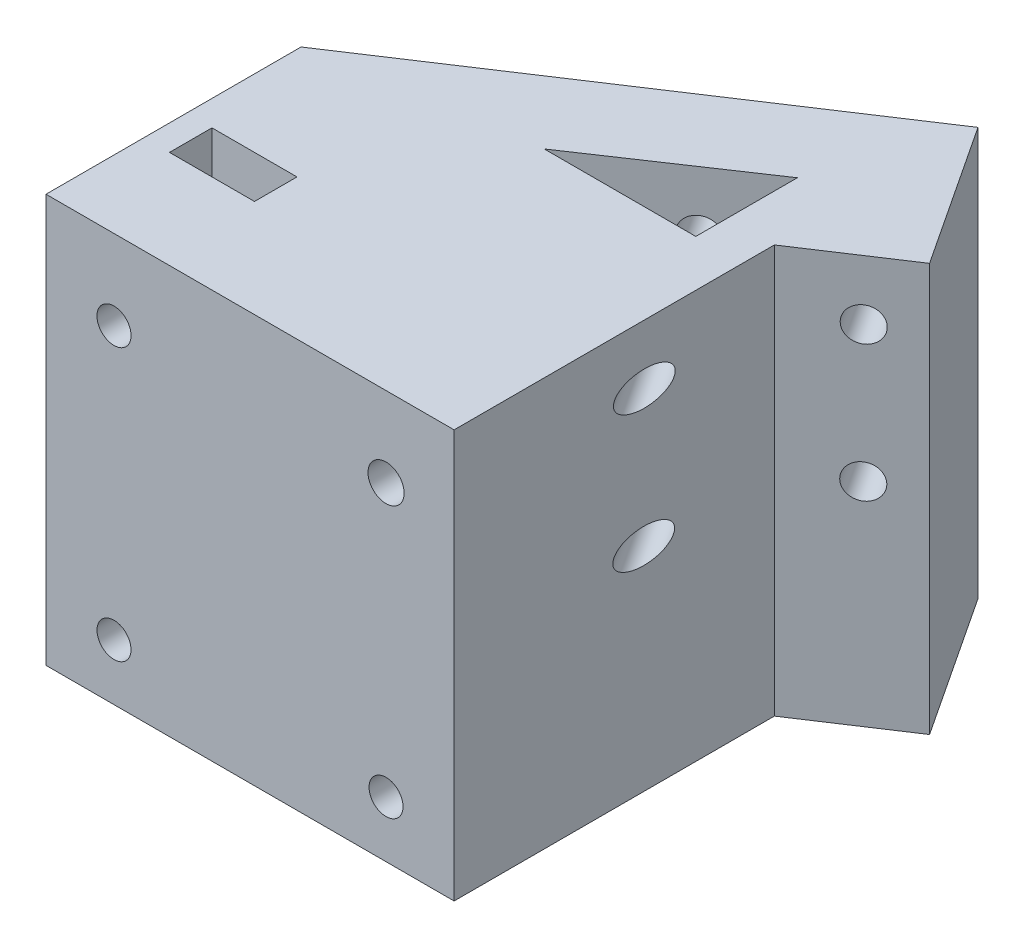
SolidWorks part; units mm, degrees
ref_plane "Front" through (0, 0, 0) normal (0, 0, 1) x (1, 0, 0)
ref_plane "Top" through (0, 0, 0) normal (0, 1, 0) x (1, 0, 0)
ref_plane "Right" through (0, 0, 0) normal (1, 0, 0) x (0, 0, -1)
sketch "Sketch1" plane through (0, 0, 0) normal (0, 1, 0) x (1, 0, 0)
  line L0 (48.006, 31.6253) -> (0, 0)
  line L1 (0, 0) -> (48.006, 0)
  line L2 (0, 0) -> (0, 31.6253)
  line L3 (0, 31.6253) -> (48.006, 31.6253)
  line L4 (48.006, 0) -> (48.006, 31.6253)
  dimension "D1" = 48.006
extrude "Boss-Extrude1" add sketch "Sketch1" along normal blind 48 contours L1 L4 L0
sketch "Sketch2" plane through (0, 0, 0) normal (0, 0, 1) x (1, 0, 0)
  line L1 (0, 0) -> (48.006, 0)
  line L2 (0, 0) -> (0, 48)
  line L3 (0, 48) -> (48.006, 48)
  line L4 (48.006, 0) -> (48.006, 48)
  circle A0 centre (8, 6.6) radius 2
  circle A1 centre (8, 38.6) radius 2.0068
  circle A2 centre (40, 6.6) radius 2
  circle A3 centre (40, 38.6) radius 2.1235
ref_plane "Plane2" through (0, 0, 0) normal (-0.5501, 0, -0.8351) x (-0.8351, 0, 0.5501)
sketch "Sketch4" plane through (0, 0, 0) normal (-0.5501, 0, -0.8351) x (-0.8351, 0, 0.5501)
  line L0 (-57.4868, 48) -> (-57.4868, 0) construction
  line L2 (-57.4868, 48) -> (0, 48) construction
  circle A0 centre (-51.8973, 40.9808) radius 2
  circle A1 centre (-42.4868, 33) radius 12.339
  circle A2 centre (-35.8955, 41.0209) radius 2
  circle A3 centre (-35.8554, 25.0192) radius 2
  circle A4 centre (-51.8571, 24.9791) radius 2
  point P17 (-43.8763, 33)
  dimension "D1" = 15
  dimension "D2" = 15
  dimension "D3" = 4
extrude "Cut-Extrude2" cut sketch "Sketch4" against normal blind 50 contours A4 | A0 | A2 | A3
extrude "Boss-Extrude2" add sketch "Sketch2" along normal blind 30
sketch "Sketch5" plane through (0, 0, 0) normal (-0.5501, 0, -0.8351) x (-0.8351, 0, 0.5501)
  circle A0 centre (-43.8571, 32.9791) radius 4
  circle A1 centre (-51.8571, 24.9791) radius 2 construction
  dimension "D1" = 8
  dimension "D2" = 8
  dimension "D3" = 8
extrude "Cut-Extrude3" cut sketch "Sketch5" against normal blind 6
sketch "Sketch6" plane through (0, 0, 0) normal (0, -1, 0) x (1, 0, 0)
  line L2 (24.6899, -3.9158) -> (42.5147, -3.9158)
  line L4 (24.6899, -3.9158) -> (42.5147, -15.8724)
  line L5 (42.5147, -15.8724) -> (42.5147, -3.9158)
extrude "Cut-Extrude4" cut sketch "Sketch6" against normal blind 70
sketch "Sketch7" plane through (0, 0, 0) normal (-0.5501, 0, -0.8351) x (-0.8351, 0, 0.5501)
  circle A0 centre (-35.8554, 25.0192) radius 2
  circle A1 centre (-35.8955, 41.0209) radius 2
extrude "Cut-Extrude5" cut sketch "Sketch7" against normal blind 70
sketch "Sketch8" plane through (0, 0, 30) normal (0, 0, 1) x (1, 0, 0)
  circle A0 centre (40, 6.6) radius 2
  circle A1 centre (40, 38.6) radius 2.1235
extrude "Cut-Extrude6" cut sketch "Sketch8" against normal blind 40
sketch "Sketch9" plane through (0, 0, 0) normal (-0.5501, 0, -0.8351) x (-0.8351, 0, 0.5501)
  line L0 (-57.4868, 48) -> (0, 48) construction
  line L1 (-57.4868, 0) -> (-47.8918, 0)
  line L2 (-57.4868, 0) -> (-57.4868, 48)
  line L3 (-57.4868, 48) -> (-47.8918, 48)
  line L4 (-47.8918, 0) -> (-47.8918, 48)
  circle A0 centre (-51.8571, 24.9791) radius 2
  circle A1 centre (-51.8973, 40.9808) radius 2
extrude "Boss-Extrude3" add sketch "Sketch9" against normal blind 20
sketch "Sketch10" plane through (11.0026, 0, 16.7016) normal (0.5501, 0, 0.8351) x (0.8351, 0, -0.5501)
  line L1 (47.8918, 48) -> (43.8918, 48)
  line L2 (47.8918, 48) -> (47.8918, 0)
  line L3 (47.8918, 0) -> (43.8918, 0)
  line L4 (43.8918, 48) -> (43.8918, 0)
extrude "Boss-Extrude4" add sketch "Sketch10" against normal blind 6
sketch "Sketch11" plane through (0, 48, 0) normal (0, 1, 0) x (1, 0, 0)
  line L0 (0, -30) -> (0, 0) construction
  line L5 (3, -18.4764) -> (13, -18.4764)
  line L6 (3, -18.4764) -> (3, -13.4764)
  line L7 (3, -13.4764) -> (13, -13.4764)
  line L8 (13, -18.4764) -> (13, -13.4764)
  dimension "D1" = 3
extrude "Cut-Extrude7" cut sketch "Sketch11" against normal blind 100
